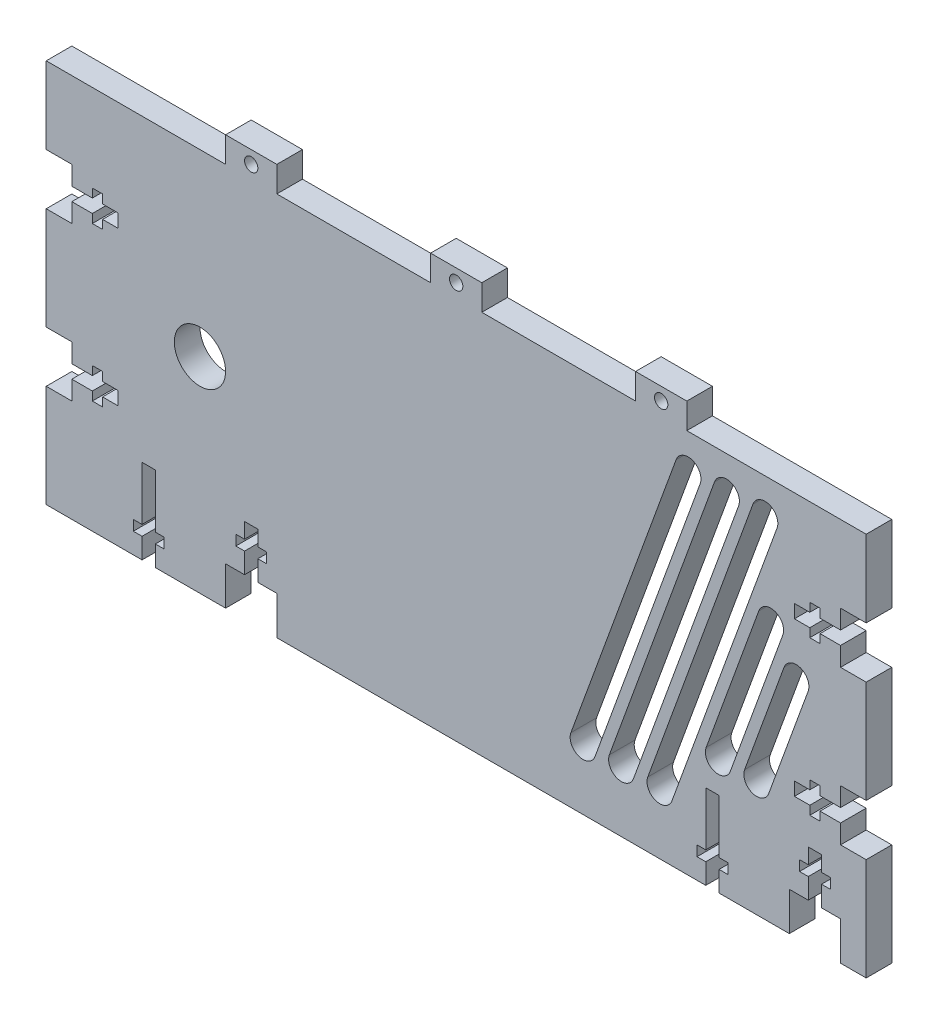
SolidWorks part; units mm, degrees
ref_plane "Front Plane" through (0, 0, 0) normal (0, 0, 1) x (1, 0, 0)
ref_plane "Top Plane" through (0, 0, 0) normal (0, 1, 0) x (1, 0, 0)
ref_plane "Right Plane" through (0, 0, 0) normal (1, 0, 0) x (0, 0, -1)
sketch "Sketch1" plane through (0, 0, 0) normal (0, 0, 1) x (1, 0, 0)
  line L0 (-101.6, 44.45) -> (-101.6, 50.8) construction
  line L1 (101.6, 50.8) -> (-101.6, 50.8)
  line L2 (101.6, 50.8) -> (101.6, -50.8)
  line L3 (101.6, -50.8) -> (-101.6, -50.8)
  line L4 (-101.6, 50.8) -> (-101.6, -50.8)
  line L5 (101.6, 50.8) -> (-101.6, -50.8) construction
  line L6 (101.6, -50.8) -> (-101.6, 50.8) construction
  point P0 (0, 0)
  dimension "D2" = 101.6
extrude "Boss-Extrude1" add sketch "Sketch1" along normal blind 6.35
sketch "Sketch3" plane through (0, 0, 6.35) normal (0, 0, 1) x (1, 0, 0)
  line L0 (101.6, 25.4) -> (95.25, 25.4)
  line L1 (101.6, -50.8) -> (101.6, 50.8) construction
  line L2 (95.25, 25.4) -> (95.25, 20.701)
  line L3 (95.25, 20.701) -> (90.17, 20.701)
  line L4 (90.17, 20.701) -> (90.17, 22.86)
  line L5 (90.17, 22.86) -> (87.63, 22.86)
  line L6 (87.63, 22.86) -> (87.63, 20.701)
  line L7 (87.63, 20.701) -> (83.82, 20.701)
  line L8 (83.82, 20.701) -> (83.82, 17.399)
  line L9 (83.82, 17.399) -> (87.63, 17.399)
  line L10 (87.63, 17.399) -> (87.63, 15.24)
  line L11 (87.63, 15.24) -> (90.17, 15.24)
  line L12 (90.17, 15.24) -> (90.17, 17.399)
  line L13 (90.17, 17.399) -> (95.25, 17.399)
  line L14 (95.25, 17.399) -> (95.25, 12.7)
  line L15 (95.25, 12.7) -> (101.6, 12.7)
  line L16 (101.6, 12.7) -> (101.6, 25.4)
  line L17 (101.6, 0) -> (0, 0) construction
  line L18 (101.6, -50.8) -> (101.6, 50.8) construction
  line L19 (98.425, 25.4) -> (98.425, 50.8) construction
  line L20 (101.6, 50.8) -> (-101.6, 50.8) construction
  line L21 (98.425, 12.7) -> (98.425, -12.7) construction
  point P29 (98.425, 0)
  dimension "D1" = 3.302
  dimension "D2" = 12.7
  dimension "D3" = 7.62
  dimension "D4" = 6.35
  dimension "D5" = 5.08
  dimension "D6" = 2.54
  dimension "D7" = 3.81
extrude "Cut-Extrude2" cut sketch "Sketch3" against normal through all
mirror "Mirror4" about plane through (0, 0, 0) normal (0, 1, 0) of "Cut-Extrude2"
mirror "Mirror1" about plane through (0, 0, 0) normal (1, 0, 0) of "Mirror4", "Cut-Extrude2"
sketch "Sketch2" plane through (0, 0, 6.35) normal (0, 0, 1) x (1, 0, 0)
  line L0 (101.6, 50.8) -> (-101.6, 50.8) construction
  line L1 (-101.6, 50.8) -> (-57.15, 50.8)
  line L2 (-101.6, 50.8) -> (-101.6, 44.45)
  line L3 (-101.6, 44.45) -> (-57.15, 44.45)
  line L4 (-57.15, 50.8) -> (-57.15, 44.45)
  line L5 (-44.45, 50.8) -> (-6.35, 50.8)
  line L6 (-44.45, 50.8) -> (-44.45, 44.45)
  line L7 (-44.45, 44.45) -> (-6.35, 44.45)
  line L8 (-6.35, 50.8) -> (-6.35, 44.45)
  line L9 (101.6, -50.8) -> (101.6, -25.4) construction
  line L10 (6.35, 50.8) -> (44.45, 50.8)
  line L11 (6.35, 50.8) -> (6.35, 44.45)
  line L12 (6.35, 44.45) -> (44.45, 44.45)
  line L13 (44.45, 50.8) -> (44.45, 44.45)
  line L14 (57.15, 50.8) -> (101.6, 50.8)
  line L15 (57.15, 50.8) -> (57.15, 44.45)
  line L16 (57.15, 44.45) -> (101.6, 44.45)
  line L17 (101.6, 50.8) -> (101.6, 44.45)
  line L18 (-57.15, 50.8) -> (-44.45, 44.45) construction
  line L19 (-6.35, 50.8) -> (6.35, 44.45) construction
  line L20 (44.45, 50.8) -> (57.15, 44.45) construction
  line L21 (0, 47.625) -> (0, 0) construction
  line L22 (-44.45, 50.8) -> (-44.45, 44.45) construction
  line L24 (-57.15, -50.8) -> (-57.15, -41.275)
  line L25 (-101.6, -50.8) -> (101.6, -50.8) construction
  line L26 (-57.15, -50.8) -> (-44.45, -50.8)
  line L27 (-44.45, -50.8) -> (-44.45, -41.275)
  line L28 (44.45, 44.45) -> (57.15, 44.45) construction
  line L29 (-44.45, -41.275) -> (-49.149, -41.275)
  line L30 (-49.149, -41.275) -> (-49.149, -36.195)
  line L31 (-49.149, -36.195) -> (-46.99, -36.195)
  line L32 (-46.99, -36.195) -> (-46.99, -33.655)
  line L37 (-46.99, -33.655) -> (-49.149, -33.655)
  line L38 (-49.149, -33.655) -> (-49.149, -29.845)
  line L39 (-49.149, -29.845) -> (-52.451, -29.845)
  line L40 (-52.451, -29.845) -> (-52.451, -33.655)
  line L41 (-52.451, -33.655) -> (-54.61, -33.655)
  line L42 (-54.61, -33.655) -> (-54.61, -36.195)
  line L43 (-54.61, -36.195) -> (-52.451, -36.195)
  line L44 (-52.451, -36.195) -> (-52.451, -41.275)
  line L45 (-52.451, -41.275) -> (-57.15, -41.275)
  line L46 (82.55, -50.8) -> (82.55, -41.275)
  line L47 (82.55, -41.275) -> (87.249, -41.275)
  line L48 (87.249, -41.275) -> (87.249, -36.195)
  line L49 (87.249, -36.195) -> (85.09, -36.195)
  line L50 (85.09, -36.195) -> (85.09, -33.655)
  line L51 (85.09, -33.655) -> (87.249, -33.655)
  line L52 (87.249, -33.655) -> (87.249, -29.845)
  line L53 (87.249, -29.845) -> (90.551, -29.845)
  line L54 (90.551, -29.845) -> (90.551, -33.655)
  line L55 (90.551, -33.655) -> (92.71, -33.655)
  line L56 (92.71, -33.655) -> (92.71, -36.195)
  line L57 (92.71, -36.195) -> (90.551, -36.195)
  line L58 (90.551, -36.195) -> (90.551, -41.275)
  line L59 (90.551, -41.275) -> (95.25, -41.275)
  line L60 (95.25, -41.275) -> (95.25, -50.8)
  line L67 (82.55, -50.8) -> (95.25, -50.8)
  line L68 (-95.25, 25.4) -> (-95.25, 20.701) construction
  line L69 (-95.25, 20.701) -> (-90.17, 20.701) construction
  line L70 (-90.17, 20.701) -> (-90.17, 22.86) construction
  line L71 (-83.82, 20.701) -> (-83.82, 17.399) construction
  line L72 (-87.63, 15.24) -> (-90.17, 15.24) construction
  line L73 (-87.63, 20.701) -> (-83.82, 20.701) construction
  line L74 (-57.15, -47.625) -> (-57.15, -41.275) construction
  line L75 (82.55, -47.625) -> (82.55, -41.275) construction
  line L76 (61.849, -29.845) -> (65.151, -29.845)
  line L77 (65.151, -29.845) -> (65.151, -43.18)
  line L78 (65.151, -43.18) -> (67.31, -43.18)
  line L79 (67.31, -43.18) -> (67.31, -45.72)
  line L80 (67.31, -45.72) -> (65.151, -45.72)
  line L81 (65.151, -45.72) -> (65.151, -50.8)
  line L82 (65.151, -50.8) -> (61.849, -50.8)
  line L83 (61.849, -50.8) -> (61.849, -45.72)
  line L84 (61.849, -45.72) -> (59.69, -45.72)
  line L85 (59.69, -45.72) -> (59.69, -43.18)
  line L86 (59.69, -43.18) -> (61.849, -43.18)
  line L87 (61.849, -43.18) -> (61.849, -29.845)
  line L88 (-77.851, -50.8) -> (-77.851, -45.72)
  line L89 (-77.851, -45.72) -> (-80.01, -45.72)
  line L90 (-80.01, -45.72) -> (-80.01, -43.18)
  line L91 (-80.01, -43.18) -> (-77.851, -43.18)
  line L92 (-77.851, -43.18) -> (-77.851, -29.845)
  line L93 (-77.851, -29.845) -> (-74.549, -29.845)
  line L94 (-74.549, -29.845) -> (-74.549, -43.18)
  line L95 (-74.549, -43.18) -> (-72.39, -43.18)
  line L96 (-72.39, -43.18) -> (-72.39, -45.72)
  line L97 (-72.39, -45.72) -> (-74.549, -45.72)
  line L98 (-74.549, -45.72) -> (-74.549, -50.8)
  line L99 (-76.2, -29.845) -> (-76.2, -50.8) construction
  line L100 (63.5, -29.845) -> (63.5, -50.8) construction
  line L101 (101.6, -50.8) -> (101.6, -25.4) construction
  line L102 (-77.851, -50.8) -> (-74.549, -50.8)
  circle A0 centre (-50.8, 47.625) radius 1.651
  circle A1 centre (0, 47.625) radius 1.651
  circle A2 centre (50.8, 47.625) radius 1.651
  dimension "D2" = 3.302
  dimension "D1" = 12.7
  dimension "D3" = 6.35
  dimension "D4" = 9.525
  dimension "D5" = 25.4
  dimension "D6" = 38.1
extrude "Cut-Extrude1" cut sketch "Sketch2" against normal through all
sketch "Sketch4" plane through (0, 0, 6.35) normal (0, 0, 1) x (1, 0, 0)
  line L0 (-101.6, 25.4) -> (-101.6, 12.7) construction
  line L1 (-101.6, 12.7) -> (-101.6, -12.7) construction
  line L2 (-63.5, 0) -> (0, 0) construction
  circle A0 centre (-63.5, 0) radius 6.35
  dimension "D1" = 12.7
  dimension "D2" = 38.1
extrude "Cut-Extrude3" cut sketch "Sketch4" against normal through all
sketch "Sketch5" plane through (0, 0, 6.35) normal (0, 0, 1) x (1, 0, 0)
  line L0 (0, 0) -> (101.6, 0) construction
  line L1 (101.6, -12.7) -> (101.6, 12.7) construction
  line L2 (50.469, -35.8023) -> (76.531, 35.8023) construction
  line L3 (47.4855, -34.7164) -> (73.5474, 36.8882)
  line L4 (53.4526, -36.8882) -> (79.5145, 34.7164)
  arc A0 (47.4855, -34.7164) -> (53.4526, -36.8882) centre (50.469, -35.8023) ccw
  arc A1 (79.5145, 34.7164) -> (73.5474, 36.8882) centre (76.531, 35.8023) ccw
  point P7 (63.5, 0)
  dimension "D1" = 3.175
  dimension "D2" = 76.2
  dimension "D3" = 38.1
  dimension "D4" = 110
extrude "Cut-Extrude4" cut sketch "Sketch5" against normal through all
pattern_linear "LPattern1" count 3 spacing 9.525 along (-1, 0, 0) of "Cut-Extrude4"
sketch "Sketch6" plane through (0, 0, 6.35) normal (0, 0, 1) x (1, 0, 0)
  line L0 (64.9358, -22.225) -> (77.9667, 13.5773) construction
  line L1 (61.9522, -21.1391) -> (74.9832, 14.6632)
  line L2 (67.9193, -23.3109) -> (80.9503, 12.4914)
  line L3 (53.4526, -36.8882) -> (79.5145, 34.7164) construction
  line L4 (57.3538, 0) -> (60.1212, 0) construction
  line L5 (43.9276, -36.8882) -> (69.9895, 34.7164) construction
  line L6 (73.5474, 36.8882) -> (47.4855, -34.7164) construction
  line L7 (66.8788, 0) -> (69.6462, 0) construction
  line L8 (65.151, -50.8) -> (82.55, -50.8) construction
  line L9 (84.234, 4.6267) -> (74.4608, -22.225) construction
  line L10 (87.2175, 3.5408) -> (77.4443, -23.3109)
  line L11 (81.2505, 5.7126) -> (71.4772, -21.1391)
  line L12 (76.4038, 0) -> (79.1712, 0) construction
  line L13 (64.9358, -22.225) -> (74.4608, -22.225) construction
  arc A0 (61.9522, -21.1391) -> (67.9193, -23.3109) centre (64.9358, -22.225) ccw
  arc A1 (80.9503, 12.4914) -> (74.9832, 14.6632) centre (77.9667, 13.5773) ccw
  arc A2 (79.5145, 34.7164) -> (73.5474, 36.8882) centre (76.531, 35.8023) ccw construction
  arc A3 (87.2175, 3.5408) -> (81.2505, 5.7126) centre (84.234, 4.6267) ccw
  arc A4 (71.4772, -21.1391) -> (77.4443, -23.3109) centre (74.4608, -22.225) ccw
  point P2 (71.4512, -4.3239)
  point P24 (79.3474, -8.7991)
  dimension "D1" = 38.1
  dimension "D2" = 28.575
  dimension "D3" = 28.575
extrude "Cut-Extrude5" cut sketch "Sketch6" against normal through all
sketch "Sketch7" plane through (0, -50.8, 0) normal (0, -1, 0) x (1, 0, 0)
  line L0 (61.849, 0) -> (65.151, 6.35) construction
  line L1 (-77.851, 0) -> (-74.549, 6.35) construction
  line L2 (-74.549, 6.35) -> (-57.15, 6.35) construction
  line L3 (-74.549, 0) -> (-74.549, 6.35) construction
  circle A0 centre (63.5, 3.175) radius 1.651 construction
  circle A1 centre (-76.2, 3.175) radius 1.651 construction
  dimension "D1" = 3.302
